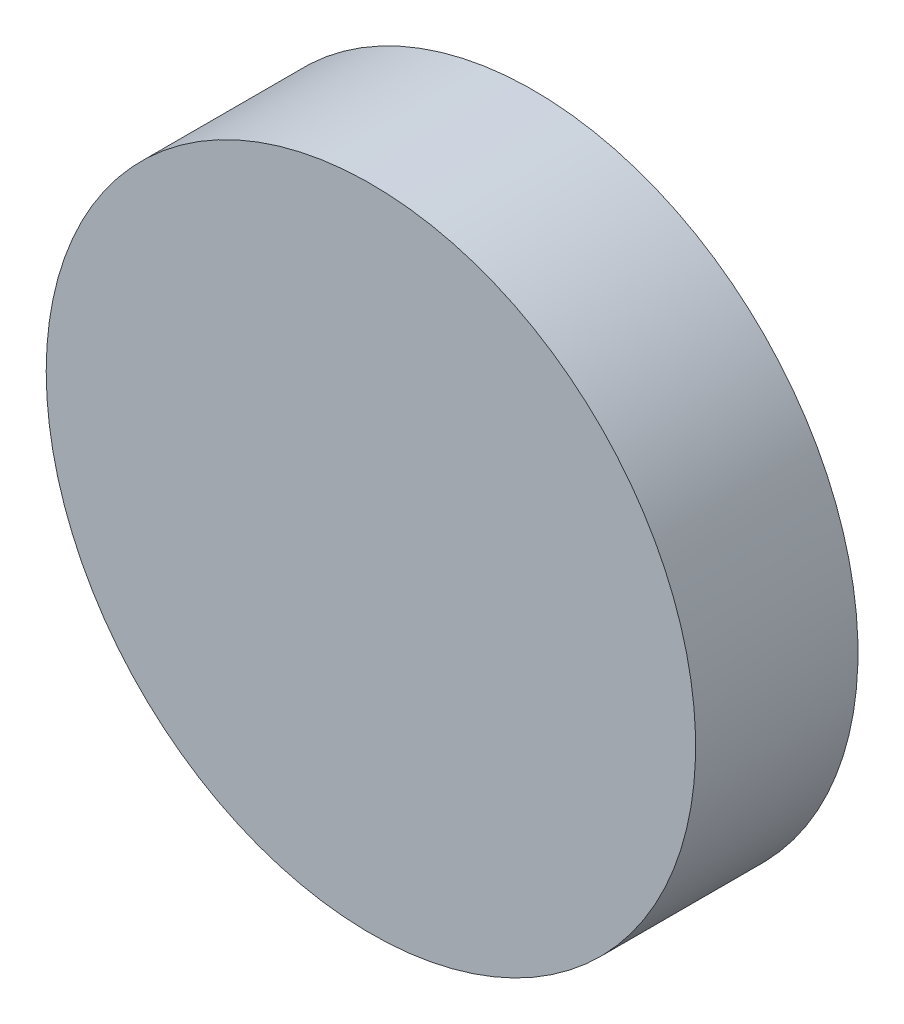
SolidWorks part; units mm, degrees
ref_plane "Front Plane" through (0, 0, 0) normal (0, 0, 1) x (1, 0, 0)
ref_plane "Top Plane" through (0, 0, 0) normal (0, 1, 0) x (1, 0, 0)
ref_plane "Right Plane" through (0, 0, 0) normal (1, 0, 0) x (0, 0, -1)
sketch "Sketch2" plane through (0, 0, 0) normal (1, 0, 0) x (0, 0, -1)
  line L0 (0, 2) -> (1, 2)
  line L1 (1, 2) -> (1, 0.875)
  line L2 (1, 0.875) -> (0.5, 0.875)
  line L3 (0.5, 0.875) -> (0.5, 0)
  line L4 (0.5, 0) -> (0, 0)
  line L5 (0, 2) -> (0, 0)
  dimension "D1" = 2
  dimension "D2" = 0.875
  dimension "D3" = 1
  dimension "D4" = 0.5
revolve "Revolve1" add sketch "Sketch2" angle 360 about L4
